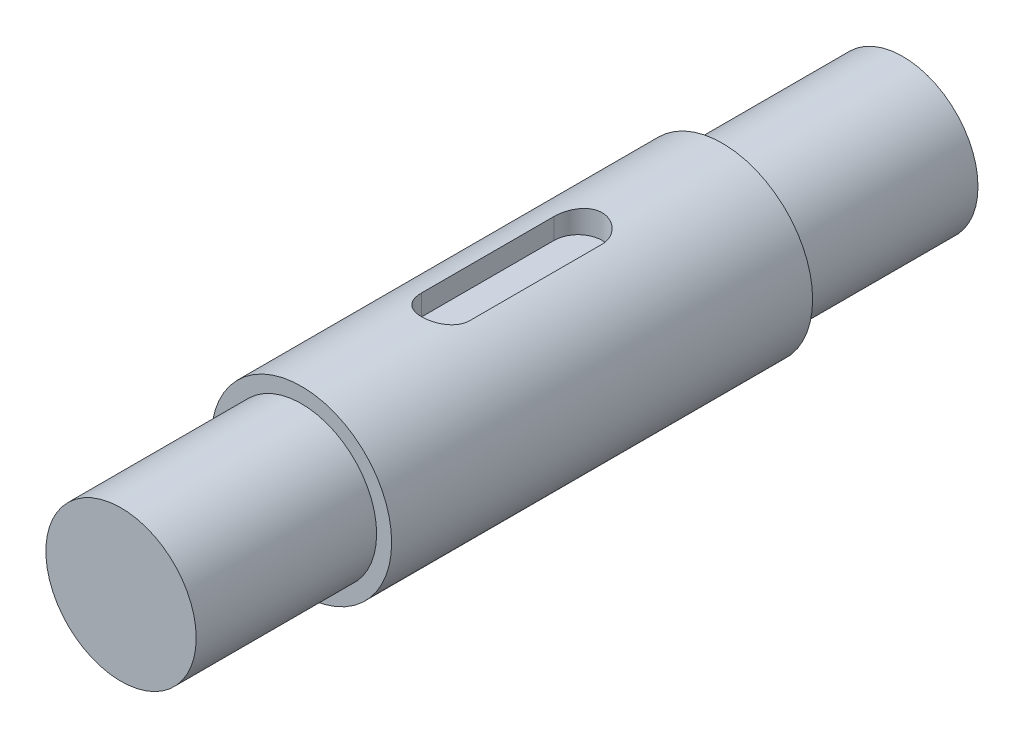
SolidWorks part; units mm, degrees
ref_plane "Front" through (0, 0, 0) normal (0, 0, 1) x (1, 0, 0)
ref_plane "Top" through (0, 0, 0) normal (0, 1, 0) x (1, 0, 0)
ref_plane "Right" through (0, 0, 0) normal (1, 0, 0) x (0, 0, -1)
sketch "Sketch1" plane through (0, 0, 0) normal (1, 0, 0) x (0, 0, -1)
  line L0 (-91.7234, 0) -> (131.233, 0) construction
  line L1 (0, 15) -> (70, 15)
  line L2 (-30, 12.5) -> (-30, 0)
  line L3 (-30, 0) -> (100, 0)
  line L4 (100, 0) -> (100, 12.5)
  line L5 (70, 15) -> (70, 12.5)
  line L6 (-30, 12.5) -> (0, 12.5)
  line L7 (0, 12.5) -> (0, 15)
  line L8 (70, 12.5) -> (100, 12.5)
  dimension "D1" = 30
  dimension "D2" = 100
  dimension "D3" = 30
  dimension "D4" = 25
  dimension "D5" = 70
revolve "Revolve1" add sketch "Sketch1" angle 360 about L0
sketch "Sketch2" plane through (0, 0, 0) normal (0, 1, 0) x (1, 0, 0)
  line L6 (0, 46) -> (0, 24) construction
  line L7 (4, 46) -> (4, 24)
  line L8 (-4, 46) -> (-4, 24)
  line L10 (-12.5, 0) -> (12.5, 0) construction
  arc A4 (4, 46) -> (-4, 46) centre (0, 46) ccw
  arc A5 (-4, 24) -> (4, 24) centre (0, 24) ccw
  point P14 (0, 35)
  dimension "D1" = 22
  dimension "D2" = 8
  dimension "D3" = 35
extrude "Cut-Extrude1" cut sketch "Sketch2" along normal through all from offset 11
